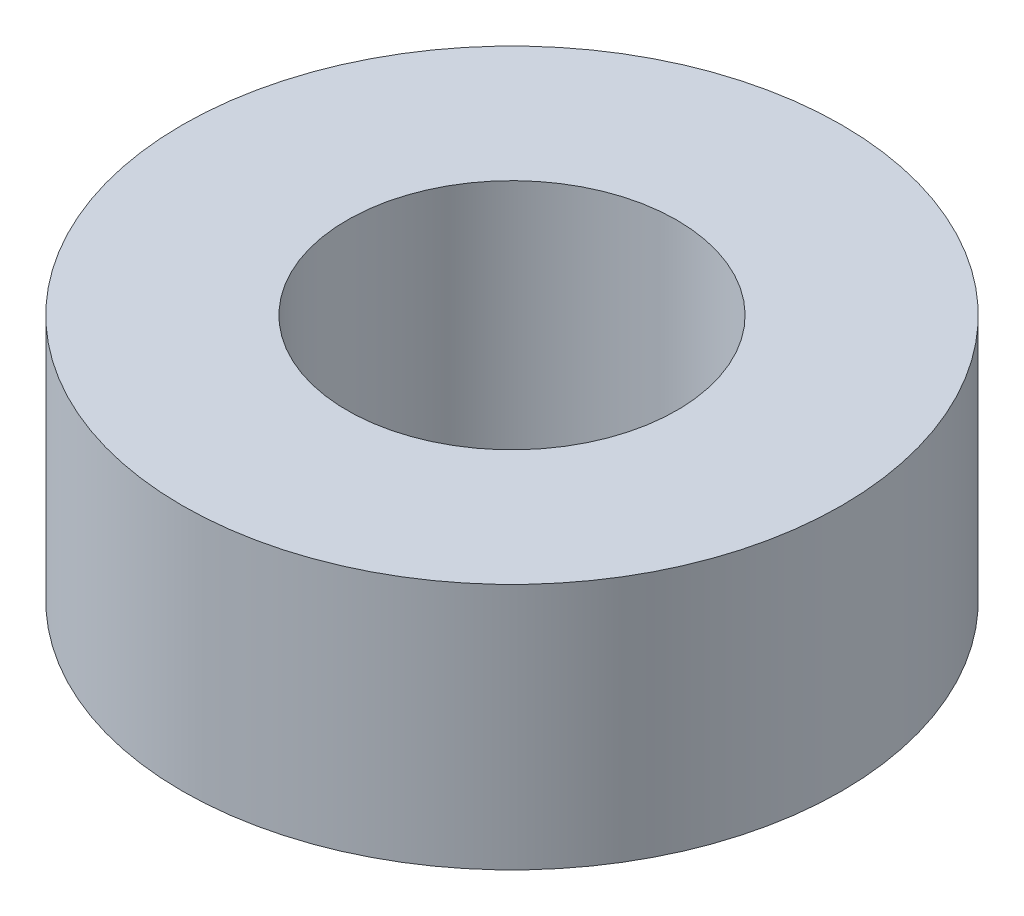
SolidWorks part; units mm, degrees
ref_plane "Front Plane" through (0, 0, 0) normal (0, 0, 1) x (1, 0, 0)
ref_plane "Top Plane" through (0, 0, 0) normal (0, 1, 0) x (1, 0, 0)
ref_plane "Right Plane" through (0, 0, 0) normal (1, 0, 0) x (0, 0, -1)
sketch "Sketch1" plane through (0, 0, 0) normal (0, 0, 1) x (1, 0, 0)
  line L0 (2, -2.5) -> (4, -2.5)
  line L1 (4, -2.5) -> (4, 0.5)
  line L2 (4, 0.5) -> (2, 0.5)
  line L3 (2, 0.5) -> (2, -2.5)
  line L4 (0, 0.8) -> (0, 0) construction
  dimension "D2" = 2
  dimension "D3" = 3
  dimension "D4" = 0.5
  dimension "D5" = 2
revolve "Revolve1" add sketch "Sketch1" angle 360 about L4
